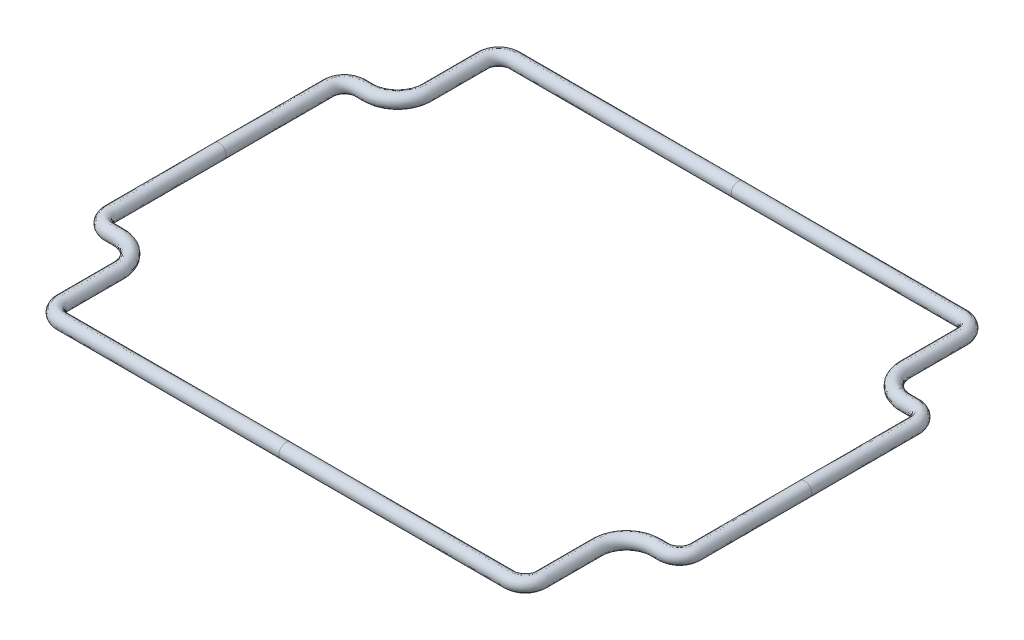
SolidWorks part; units mm, degrees
material "POLYURETHANE (11671)"
ref_plane "Front Plane" through (0, 0, 0) normal (0, 0, 1) x (1, 0, 0)
ref_plane "Top Plane" through (0, 0, 0) normal (0, 1, 0) x (1, 0, 0)
ref_plane "Right Plane" through (0, 0, 0) normal (1, 0, 0) x (0, 0, -1)
sketch "BeltPathS" plane through (0, 0, 0) normal (0, 1, 0) x (1, 0, 0)
  line L6 (0, 42.5) -> (-42, 42.5)
  line L7 (-45, 39.5) -> (-45, 29)
  line L8 (-50.5, 23.5) -> (-52, 23.5)
  line L9 (-55, 20.5) -> (-55, 0)
  line L12 (0, 0) -> (0, 42.5) construction
  line L13 (0, 0) -> (-55, 0) construction
  arc A6 (-42, 42.5) -> (-45, 39.5) centre (-42, 39.5) ccw
  arc A7 (-50.5, 23.5) -> (-45, 29) centre (-50.5, 29) ccw
  arc A8 (-52, 23.5) -> (-55, 20.5) centre (-52, 20.5) ccw
  dimension "R2" = 5.5
  dimension "R1" = 3
  dimension "R3" = 3
  dimension "D3" = 19
  dimension "XDim" = 85
  dimension "YDim" = 110
  dimension "D6" = 10
sketch "QuarterBeltProfile" plane through (0, 0, 0) normal (0, 0, -1) x (-1, 0, 0)
  circle A0 centre (55, 0) radius 1.3
  dimension "Diameter" = 2.6
sweep "Quarter O-Ring" add profiles "QuarterBeltProfile" path "BeltPathS"
mirror "QO HM" about plane through (0, 0, 0) normal (1, 0, 0) of "Quarter O-Ring"
mirror "QO VM" about plane through (0, 0, 0) normal (0, 0, 1) of "QO HM", "Quarter O-Ring"
